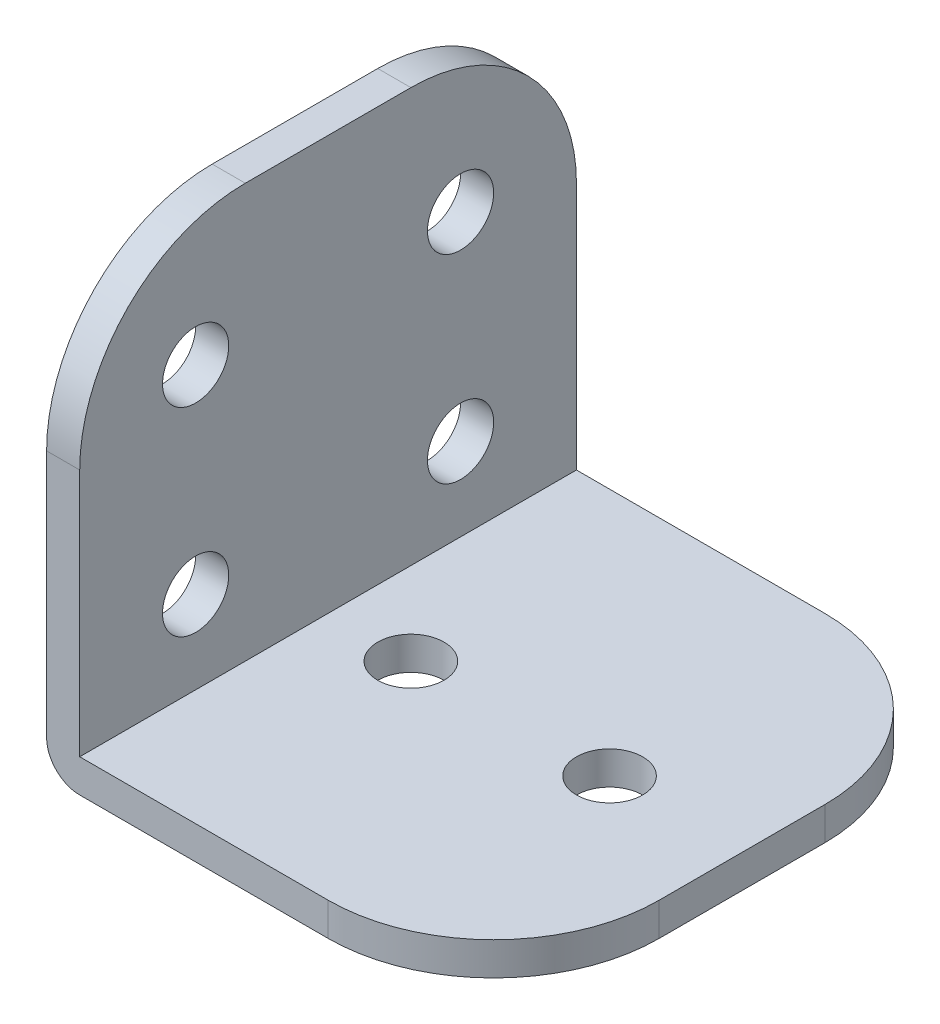
SolidWorks part; units mm, degrees
ref_plane "Plan de face" through (0, 0, 0) normal (0, 0, 1) x (1, 0, 0)
ref_plane "Plan de dessus" through (0, 0, 0) normal (0, 1, 0) x (1, 0, 0)
ref_plane "Plan de droite" through (0, 0, 0) normal (1, 0, 0) x (0, 0, -1)
sketch "Esquisse1" plane through (0, 0, 0) normal (0, 0, 1) x (1, 0, 0)
  line L0 (0, 2) -> (0, 27)
  line L1 (2, 0) -> (27, 0)
  line L2 (2, 2) -> (27, 2)
  line L3 (2, 2) -> (2, 27)
  line L4 (0, 27) -> (2, 27)
  line L5 (27, 2) -> (27, 0)
  arc A0 (0, 2) -> (2, 0) centre (2, 2) ccw
  arc A1 (2, 2) -> (2, 2) centre (2, 2) ccw
  point P6 (0, 0)
  dimension "D2" = 2
  dimension "D1" = 27
  dimension "D4" = 27
  dimension "D3" = 2
extrude "Boss.-Extru.1" add sketch "Esquisse1" along normal mid plane 30
fillet "Congé1" radius 10 4 edges at (1, 27, -15) (1, 27, 15) (27, 1, -15) (27, 1, 15)
sketch "Sketch4" plane through (0, 2, 0) normal (0, 1, 0) x (1, 0, 0)
  line L0 (27, 0) -> (19, 0) construction
  line L3 (27, -5) -> (27, 5) construction
  line L4 (19, 0) -> (7, 0) construction
  circle A1 centre (7, 0) radius 2
  circle A2 centre (19, 0) radius 2
  dimension "D1" = 12
  dimension "D3" = 4
  dimension "D4" = 4
  dimension "D2" = 8
extrude "Cut-Extrude3" cut sketch "Sketch4" against normal blind 10
sketch "Sketch5" plane through (2, 0, 0) normal (1, 0, 0) x (0, 0, -1)
  line L0 (0, 27) -> (0, 19) construction
  line L1 (-5, 27) -> (5, 27) construction
  line L2 (0, 19) -> (0, 7) construction
  line L3 (-8, 27) -> (-8, 19) construction
  line L4 (-8, 19) -> (-8, 7) construction
  line L5 (8, 27) -> (8, 19) construction
  line L6 (8, 19) -> (8, 7) construction
  circle A0 centre (-8, 19) radius 2
  circle A1 centre (8, 19) radius 2
  circle A2 centre (8, 7) radius 2
  circle A3 centre (-8, 7) radius 2
  dimension "D5" = 4
  dimension "D6" = 4
  dimension "D7" = 4
  dimension "D8" = 4
  dimension "D1" = 8
  dimension "D2" = 12
  dimension "D3" = 8
  dimension "D4" = 8
extrude "Cut-Extrude4" cut sketch "Sketch5" against normal blind 10
